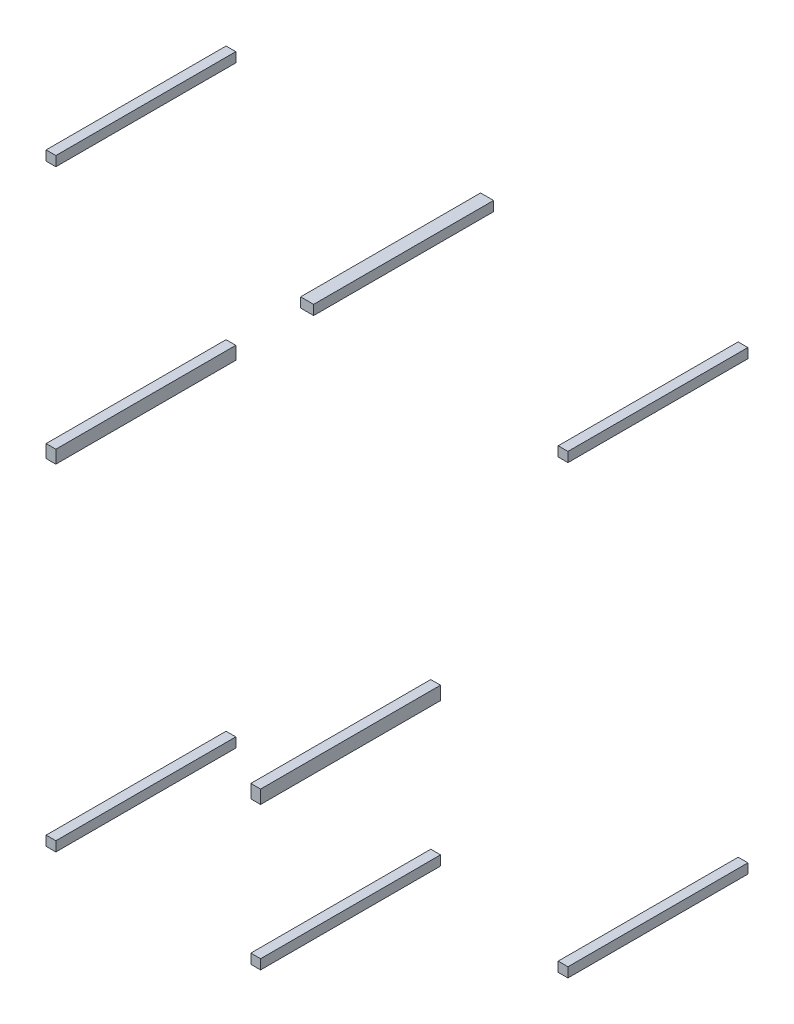
SolidWorks part; units mm, degrees
ref_plane "Спереди" through (0, 0, 0) normal (0, 0, 1) x (1, 0, 0)
ref_plane "Сверху" through (0, 0, 0) normal (0, 1, 0) x (1, 0, 0)
ref_plane "Справа" through (0, 0, 0) normal (1, 0, 0) x (0, 0, -1)
sketch "Эскиз1" plane through (0, 0, 0) normal (0, 0, 1) x (1, 0, 0)
  line L0 (4165, 0) -> (4165, -200) construction
  line L1 (200, -200) -> (50, -200)
  line L2 (200, -200) -> (200, -50)
  line L3 (200, -50) -> (50, -50)
  line L4 (50, -200) -> (50, -50)
  line L5 (3965, -200) -> (4165, -200)
  line L6 (3965, -200) -> (3965, -50)
  line L7 (3965, -50) -> (4165, -50)
  line L8 (4165, -200) -> (4165, -50)
  line L9 (3199, -6915) -> (3399, -6915) construction
  line L10 (7927, -203) -> (8077, -203)
  line L11 (7927, -203) -> (7927, -53)
  line L12 (7927, -53) -> (8077, -53)
  line L13 (8077, -203) -> (8077, -53)
  line L14 (3199, -6915) -> (3349, -6915)
  line L15 (3199, -6915) -> (3199, -7121)
  line L16 (3199, -7121) -> (3349, -7121)
  line L17 (3349, -6915) -> (3349, -7121)
  line L18 (3399, -7121) -> (3199, -7121) construction
  line L19 (0, -3962) -> (200, -3962) construction
  line L20 (7927, -6918) -> (8077, -6918)
  line L21 (7927, -6918) -> (7927, -7068)
  line L22 (7927, -7068) -> (8077, -7068)
  line L23 (8077, -6918) -> (8077, -7068)
  line L24 (3199, -9175) -> (3349, -9175)
  line L25 (3199, -9175) -> (3199, -9325)
  line L26 (3199, -9325) -> (3349, -9325)
  line L27 (3349, -9175) -> (3349, -9325)
  line L28 (200, -9178) -> (50, -9178)
  line L29 (200, -9178) -> (200, -9328)
  line L30 (200, -9328) -> (50, -9328)
  line L31 (50, -9178) -> (50, -9328)
  line L32 (50, -3962) -> (200, -3962)
  line L33 (50, -3962) -> (50, -4162)
  line L34 (50, -4162) -> (200, -4162)
  line L35 (200, -3962) -> (200, -4162)
  line L36 (200, -4162) -> (0, -4162) construction
  dimension "D1" = 150
  dimension "D2" = 150
  dimension "D3" = 150
  dimension "D4" = 150
  dimension "D5" = 150
  dimension "D6" = 150
  dimension "D7" = 150
  dimension "D8" = 150
extrude "Бобышка-Вытянуть1" add sketch "Эскиз1" along normal up to surface (2768 mm away)
